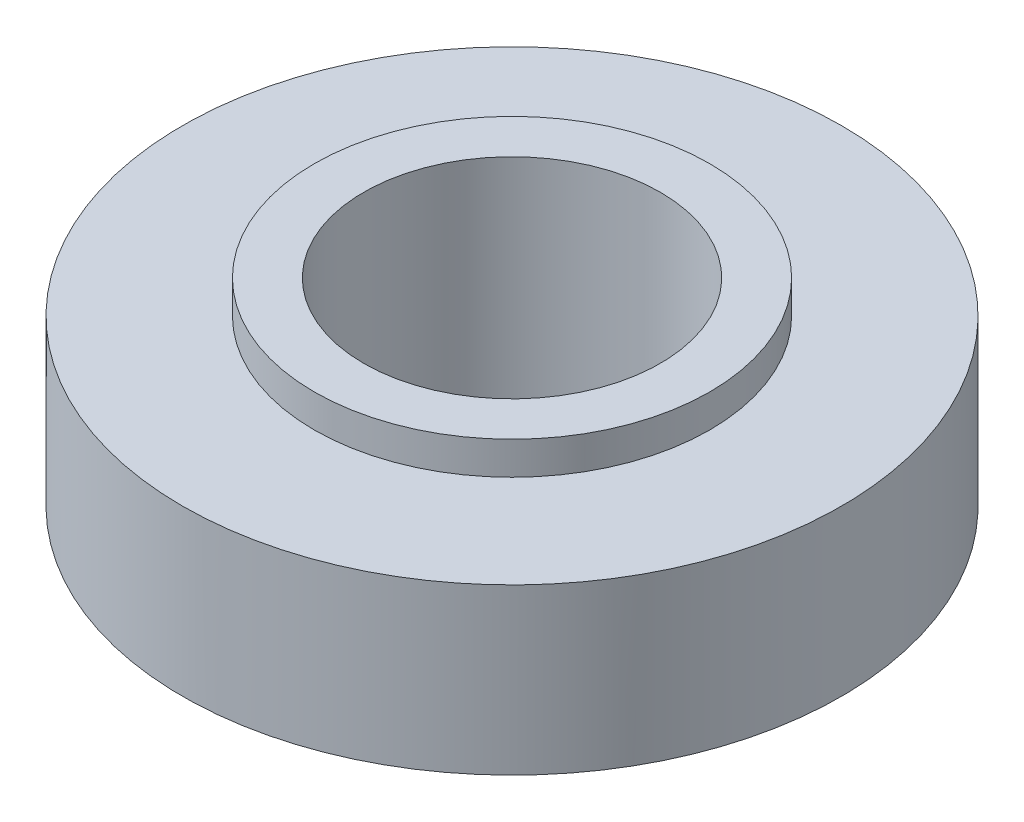
SolidWorks part; units mm, degrees
ref_plane "Front Plane" through (0, 0, 0) normal (0, 0, 1) x (1, 0, 0)
ref_plane "Top Plane" through (0, 0, 0) normal (0, 1, 0) x (1, 0, 0)
ref_plane "Right Plane" through (0, 0, 0) normal (1, 0, 0) x (0, 0, -1)
sketch "Sketch1" plane through (0, 0, 0) normal (0, 1, 0) x (1, 0, 0)
  circle A0 centre (0, 0) radius 4.5
  circle A1 centre (0, 0) radius 10
  dimension "D1" = 20
  dimension "D2" = 9
extrude "Boss-Extrude1" add sketch "Sketch1" along normal mid plane 7
sketch "Sketch2" plane through (0, 3.5, 0) normal (0, 1, 0) x (1, 0, 0)
  circle A0 centre (0, 0) radius 6
  circle A1 centre (0, 0) radius 13
  dimension "D1" = 12
  dimension "D2" = 26
extrude "Cut-Extrude1" cut sketch "Sketch2" against normal blind 1
mirror "Mirror1" about plane through (0, 0, 0) normal (0, 1, 0) of "Cut-Extrude1"
